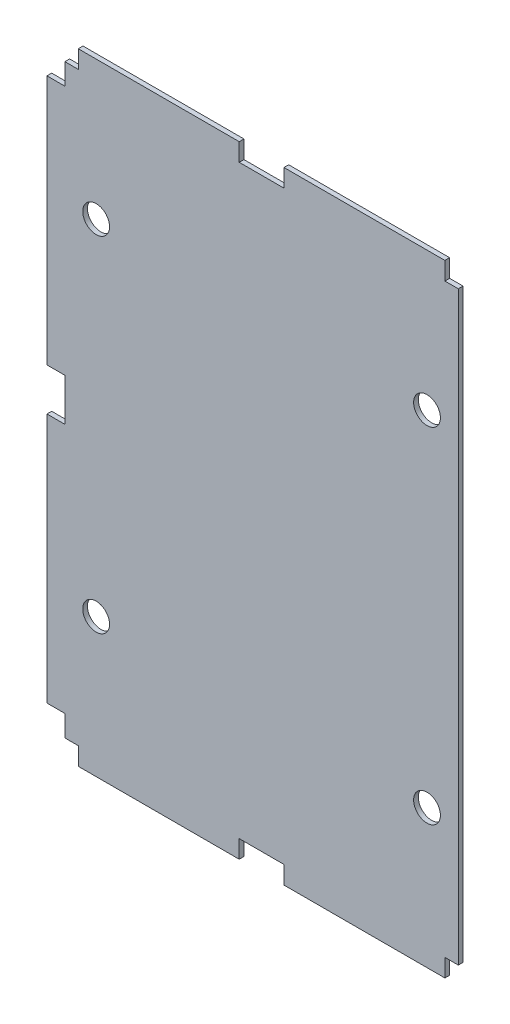
SolidWorks part; units mm, degrees
ref_plane "Front Plane" through (0, 0, 0) normal (0, 0, 1) x (1, 0, 0)
ref_plane "Top Plane" through (0, 0, 0) normal (0, 1, 0) x (1, 0, 0)
ref_plane "Right Plane" through (0, 0, 0) normal (1, 0, 0) x (0, 0, -1)
sketch "Sketch1" plane through (0, 0, 0) normal (0, 0, 1) x (1, 0, 0)
  line L0 (0, 0) -> (0, 207.9625) construction
  line L1 (-139.7, -207.9625) -> (139.7, -207.9625)
  line L2 (-139.7, -207.9625) -> (-139.7, 207.9625)
  line L3 (-139.7, 207.9625) -> (139.7, 207.9625)
  line L4 (139.7, -207.9625) -> (139.7, 207.9625)
  line L5 (-139.7, -207.9625) -> (139.7, 207.9625) construction
  line L6 (-139.7, 207.9625) -> (139.7, -207.9625) construction
  line L7 (-130.175, 207.9625) -> (-15.875, 207.9625)
  line L8 (-130.175, 207.9625) -> (-130.175, 220.6625)
  line L9 (-130.175, 220.6625) -> (-15.875, 220.6625)
  line L10 (-15.875, 207.9625) -> (-15.875, 220.6625)
  line L11 (15.875, 207.9625) -> (130.175, 207.9625)
  line L12 (15.875, 207.9625) -> (15.875, 220.6625)
  line L13 (15.875, 220.6625) -> (130.175, 220.6625)
  line L14 (130.175, 207.9625) -> (130.175, 220.6625)
  line L15 (0, 207.9625) -> (0, -207.9625) construction
  line L16 (0, 0) -> (-139.7, 0) construction
  line L17 (-139.7, 0) -> (139.7, 0) construction
  line L18 (139.7, 207.9625) -> (139.7, 112.7125) construction
  line L19 (-15.875, -207.9625) -> (-130.175, -207.9625)
  line L20 (-15.875, -207.9625) -> (-15.875, -220.6625)
  line L21 (-15.875, -220.6625) -> (-130.175, -220.6625)
  line L22 (-130.175, -207.9625) -> (-130.175, -220.6625)
  line L23 (130.175, -207.9625) -> (15.875, -207.9625)
  line L24 (130.175, -207.9625) -> (130.175, -220.6625)
  line L25 (130.175, -220.6625) -> (15.875, -220.6625)
  line L26 (15.875, -207.9625) -> (15.875, -220.6625)
  line L27 (-139.7, 192.8812) -> (-152.4, 192.8812)
  line L28 (-139.7, 192.8812) -> (-139.7, 15.0812)
  line L29 (-139.7, 15.0812) -> (-152.4, 15.0812)
  line L30 (-152.4, 192.8812) -> (-152.4, 15.0812)
  line L31 (-139.7, -15.0813) -> (-152.4, -15.0813)
  line L32 (-139.7, -15.0813) -> (-139.7, -192.8812)
  line L33 (-139.7, -192.8812) -> (-152.4, -192.8812)
  line L34 (-152.4, -15.0813) -> (-152.4, -192.8812)
  line L35 (139.7, 112.7125) -> (-139.7, 112.7125) construction
  line L36 (139.7, -112.7125) -> (-139.7, -112.7125) construction
  circle A0 centre (117.475, 122.2375) radius 9.525
  circle A1 centre (117.475, -122.2375) radius 9.525
  circle A2 centre (-117.475, -122.2375) radius 9.525
  circle A3 centre (-117.475, 122.2375) radius 9.525
  point P0 (0, 0)
  point P35 (-146.05, 192.8812)
  point P36 (139.7, -112.7125)
  point P41 (117.475, 112.7125)
  point P42 (117.475, 112.7125)
  point P43 (117.475, 112.7125)
  point P44 (139.7, 112.7125)
  point P46 (139.7, 112.7125)
  point P54 (0, 0)
  point P55 (0, 0)
  dimension "D23" = 19.05
  dimension "D22" = 22.225
  dimension "D1" = 415.925
  dimension "D2" = 279.4
  dimension "D3" = 114.3
  dimension "D4" = 114.3
  dimension "D5" = 9.525
  dimension "D6" = 9.525
  dimension "D7" = 12.7
  dimension "D8" = 12.7
  dimension "D9" = 9.525
  dimension "D10" = 12.7
  dimension "D11" = 9.525
  dimension "D12" = 12.7
  dimension "D13" = 114.3
  dimension "D14" = 114.3
  dimension "D15" = 177.8
  dimension "D16" = 177.8
  dimension "D17" = 15.0812
  dimension "D18" = 15.0812
  dimension "D19" = 12.7
  dimension "D20" = 12.7
  dimension "D21" = 95.25
extrude "Boss-Extrude3" add sketch "Sketch1" along normal blind 3.3528 contours L1 L4 L3 L2 A1 A0 A2 A3 | L27 L30 L29 L2 | L3 L10 L9 L8 | L31 L34 L33 L2 | L3 L14 L13 L12 | L1 L22 L21 L20 | L1 L26 L25 L24
